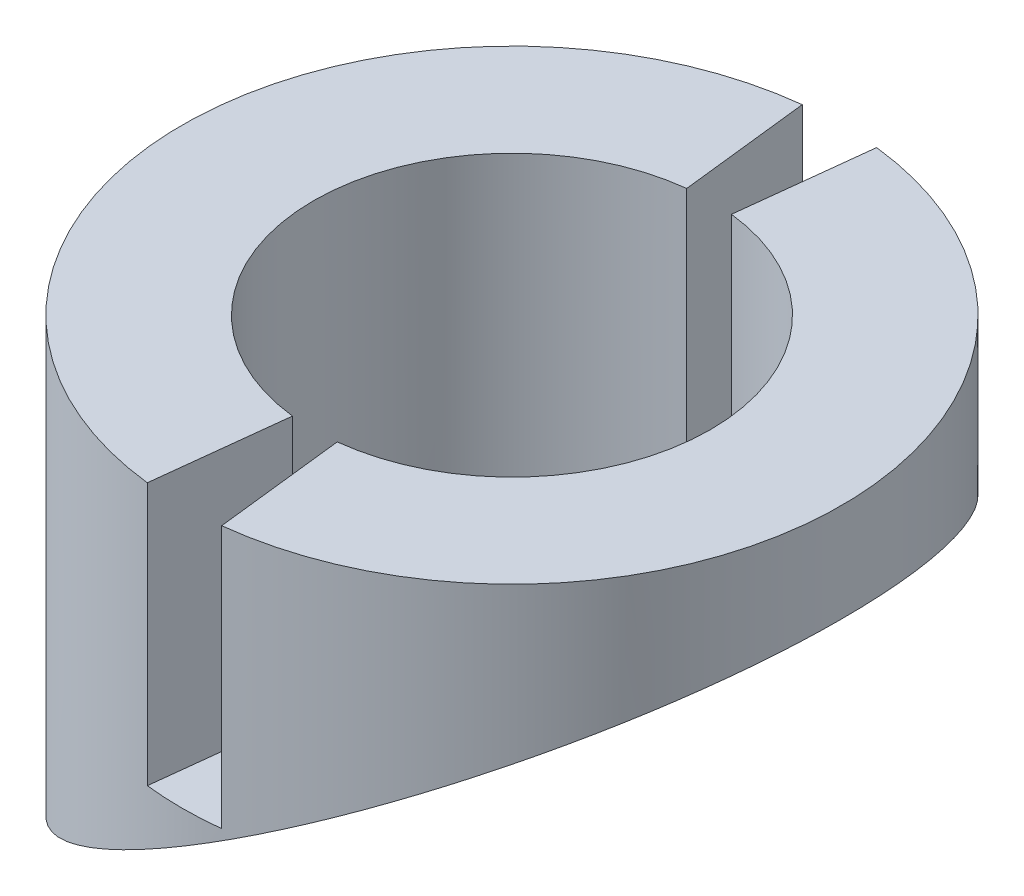
SolidWorks part; units mm, degrees
ref_plane "Front Plane" through (0, 0, 0) normal (0, 0, 1) x (1, 0, 0)
ref_plane "Top Plane" through (0, 0, 0) normal (0, 1, 0) x (1, 0, 0)
ref_plane "Right Plane" through (0, 0, 0) normal (1, 0, 0) x (0, 0, -1)
sketch "Sketch1" plane through (0, 0, 0) normal (0, 1, 0) x (1, 0, 0)
  circle A0 centre (0, 0) radius 6.05
  circle A1 centre (0, 0) radius 10.05
  dimension "D1" = 12.1
  dimension "D2" = 4
extrude "Boss-Extrude1" add sketch "Sketch1" along normal blind 15
sketch "Sketch3" plane through (0, 0, 0) normal (0, 0, 1) x (1, 0, 0)
  line L0 (-10.05, 0) -> (10.05, 12)
  line L1 (10.05, 0) -> (10.05, 15) construction
  line L2 (10.05, 12) -> (10.05, 0)
  line L3 (10.05, 0) -> (-10.05, 0)
  dimension "D1" = 12
sketch "Sketch6" plane through (0, 15, 0) normal (0, 1, 0) x (1, 0, 0)
  line L0 (-0.6373, 5.6108) -> (0.6373, 5.6108)
  line L1 (0.6373, 5.6108) -> (1.2157, 10.7035)
  line L2 (1.2157, 10.7035) -> (-1.2157, 10.7035)
  line L3 (0, -12.985) -> (0, 12.985) construction
  line L4 (-0.6373, 5.6108) -> (-1.2157, 10.7035)
  line L5 (-11.7237, 0) -> (13.1699, 0) construction
  line L6 (-0.6373, -5.6108) -> (-1.2157, -10.7035)
  line L7 (1.2157, -10.7035) -> (-1.2157, -10.7035)
  line L8 (0.6373, -5.6108) -> (1.2157, -10.7035)
  line L9 (-0.6373, -5.6108) -> (0.6373, -5.6108)
  point P8 (0, 10.7035)
  point P9 (0, 5.6108)
  point P12 (0, 0)
  point P16 (0, -5.6108)
  point P17 (0, -10.7035)
extrude "Cut-Extrude2" cut sketch "Sketch6" against normal blind 8
extrude "Cut-Extrude3" cut sketch "Sketch3" against normal mid plane 30
